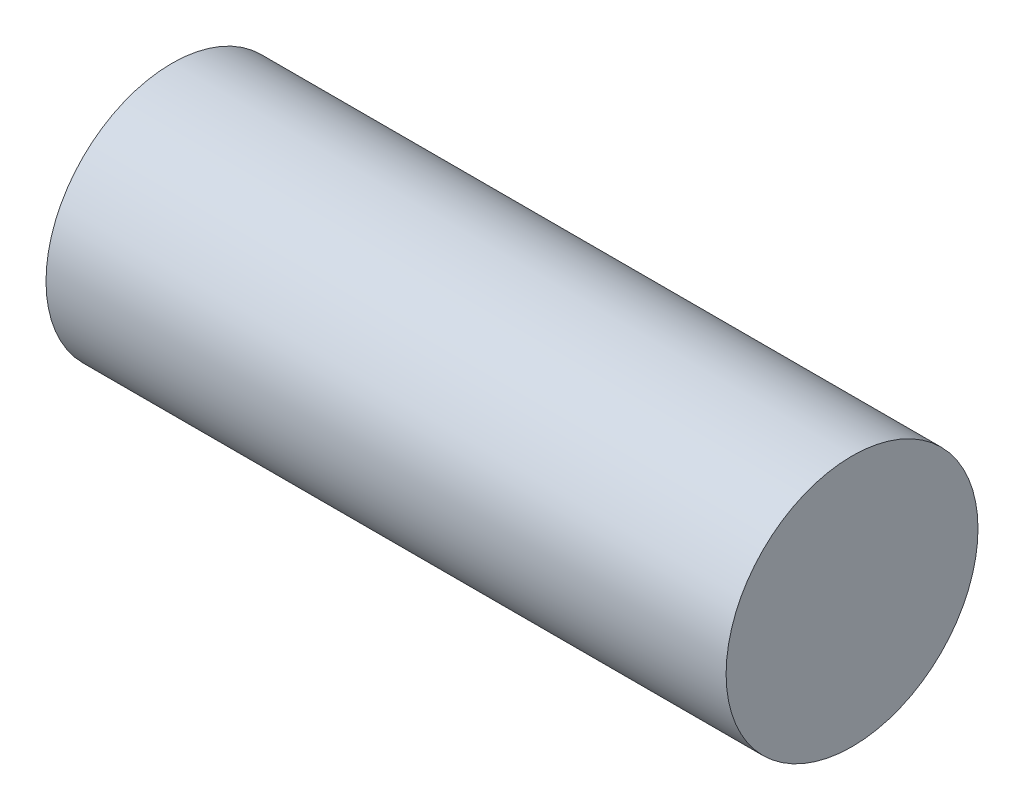
SolidWorks part; units mm, degrees
ref_plane "정면" through (0, 0, 0) normal (0, 0, 1) x (1, 0, 0)
ref_plane "윗면" through (0, 0, 0) normal (0, 1, 0) x (1, 0, 0)
ref_plane "우측면" through (0, 0, 0) normal (1, 0, 0) x (0, 0, -1)
sketch "Sketch1" plane through (0, 0, 0) normal (1, 0, 0) x (0, 0, -1)
  circle A0 centre (0, 0) radius 5
  dimension "D1" = 10
extrude "Boss-Extrude1" add sketch "Sketch1" along normal blind 27
